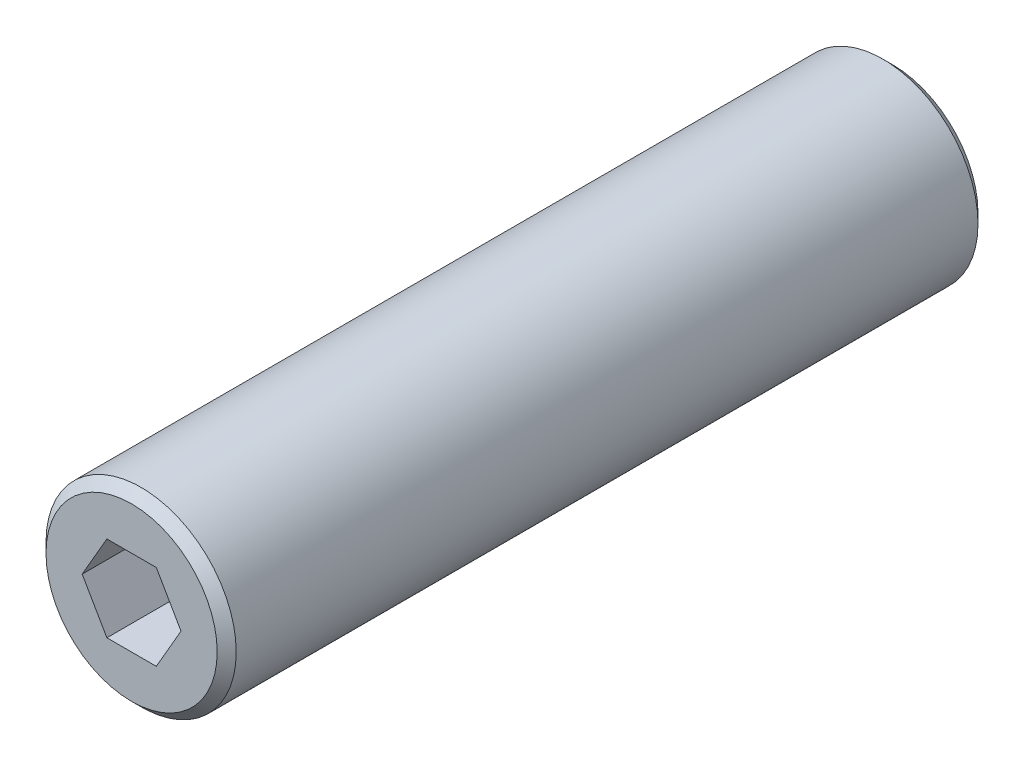
SolidWorks part; units mm, degrees
material "AISI 304"
ref_plane "前视基准面" through (0, 0, 0) normal (0, 0, 1) x (1, 0, 0)
ref_plane "上视基准面" through (0, 0, 0) normal (0, 1, 0) x (1, 0, 0)
ref_plane "右视基准面" through (0, 0, 0) normal (1, 0, 0) x (0, 0, -1)
sketch "草图1" plane through (0, 0, 0) normal (0, 0, 1) x (1, 0, 0)
  circle A0 centre (0, 0) radius 1
  dimension "D1" = 2
extrude "凸台-拉伸1" add sketch "草图1" along normal mid plane 8
cosmetic thread "装饰螺纹线1" parameters "D2"=1.221
sketch "草图2" plane through (0, 0, 4) normal (0, 0, 1) x (1, 0, 0)
  line L1 (0.2598, 0.45) -> (-0.2598, 0.45)
  line L2 (-0.2598, 0.45) -> (-0.5196, 0)
  line L3 (-0.5196, 0) -> (-0.2598, -0.45)
  line L4 (-0.2598, -0.45) -> (0.2598, -0.45)
  line L5 (0.2598, -0.45) -> (0.5196, 0)
  line L6 (0.5196, 0) -> (0.2598, 0.45)
  circle A0 centre (0, 0) radius 0.45 construction
  dimension "D1" = 0.9
extrude "切除-拉伸1" cut sketch "草图2" against normal blind 0.8
chamfer "倒角1" distance 0.1 angle 45 2 edges at (1, 0, 4) (1, 0, -4)
